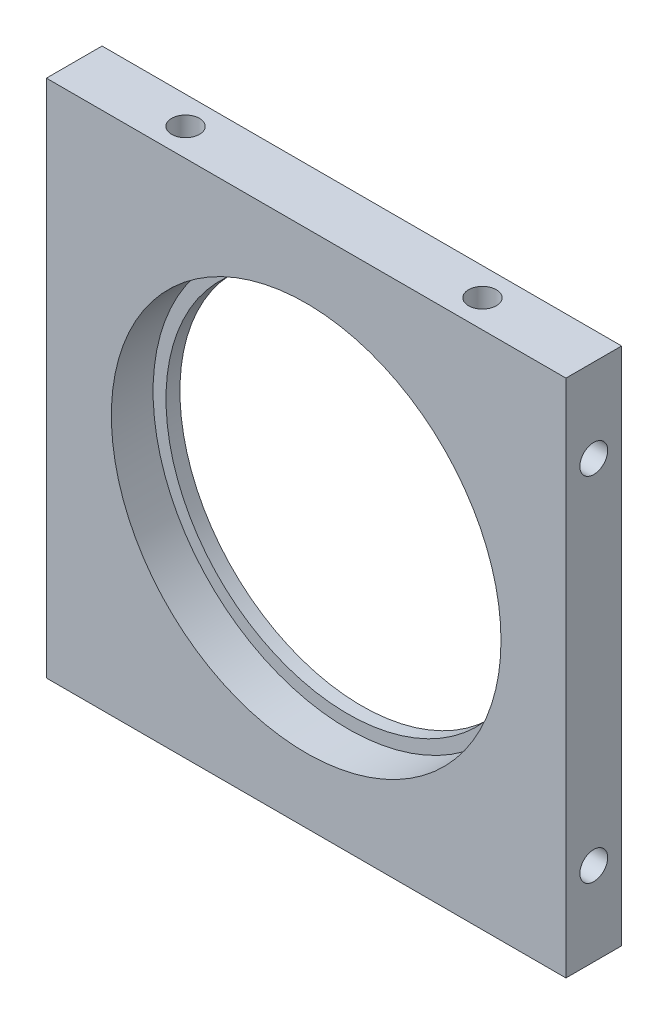
SolidWorks part; units mm, degrees
material "3.1325 (EN-AW 2017A)"
ref_plane "正面" through (0, 0, 0) normal (0, 0, 1) x (1, 0, 0)
ref_plane "平面" through (0, 0, 0) normal (0, 1, 0) x (1, 0, 0)
ref_plane "右側面" through (0, 0, 0) normal (1, 0, 0) x (0, 0, -1)
sketch "ｽｹｯﾁ2" plane through (0, 0, 0) normal (0, 0, 1) x (1, 0, 0)
  line L0 (0, 0) -> (39423.5933, 0) construction
  line L1 (0, 0) -> (0, -39423.5933) construction
  line L3 (-28, 28) -> (28, 28)
  line L4 (-28, 28) -> (-28, -28)
  line L5 (-28, -28) -> (28, -28)
  line L6 (28, 28) -> (28, -28)
  point P9 (0, 28)
  point P10 (0, 0)
  point P11 (28, 0)
  point P12 (0, 19)
  point P13 (0, -19)
  point P14 (-16, 0)
  point P15 (16, 0)
  dimension "D1" = 56
  dimension "D2" = 38
  dimension "D3" = 32
extrude "ﾎﾞｽ - 押し出し1" add sketch "ｽｹｯﾁ2" along normal mid plane 6
sketch "ｽｹｯﾁ3" plane through (0, 0, 0) normal (1, 0, 0) x (0, 0, -1)
  line L0 (0, 0) -> (4.9548, 0) construction
  line L1 (-3, 21) -> (1.5, 21)
  line L2 (-3, -28) -> (-3, 28) construction
  line L3 (1.5, 21) -> (1.5, 19.61)
  line L4 (1.5, 19.61) -> (3, 19.61)
  line L5 (3, -28) -> (3, 28) construction
  line L6 (-3, 21) -> (-3, 0)
  line L7 (-3, 0) -> (3, 0)
  line L8 (3, 0) -> (3, 19.61)
  dimension "D1" = 39.22
  dimension "D2" = 42
  dimension "D3" = 1.5
revolve "ｶｯﾄ - 回転1" cut sketch "ｽｹｯﾁ3" angle 360 about L0
hole_wizard "M3x0.5 ねじ穴1" positions "3Dｽｹｯﾁ1" profile "ｽｹｯﾁ5" tap size "M3x0.5" standard "JIS"
sketch3d "3Dｽｹｯﾁ1"
  point P0 (-16, 28, 0)
  point P4 (16, 28, 0)
  point P6 (28, 19, 0)
  point P10 (28, -19, 0)
  point P12 (16, -28, 0)
  point P16 (-16, -28, 0)
  point P24 (-28, 19, 0)
  point P26 (-28, -19, 0)
sketch "ｽｹｯﾁ5" plane through (-16, 28, 0) normal (1, 0, 0) x (0, 0, 1)
  line L0 (0, 0) -> (0, 9.2511)
  line L1 (0, 9.2511) -> (1.25, 8.5)
  line L2 (1.25, 8.5) -> (1.25, 6)
  line L3 (1.25, 6) -> (1.5, 6)
  line L4 (1.5, 6) -> (1.5, 0)
  line L5 (1.5, 0) -> (0, 0)
  line L10 (0, 9.2511) -> (-1.25, 8.5) construction
  line L11 (0, -6.35) -> (0, 107.95) construction
  dimension "ねじ下穴ﾄﾞﾘﾙ直径" = 2.5
  dimension "ねじ下穴ﾄﾞﾘﾙの深さ" = 8.5
  dimension "ねじ山の主要直径" = 3
  dimension "ねじ山の深さ" = 6
  dimension "ﾄﾞﾘﾙ角度" = 118
